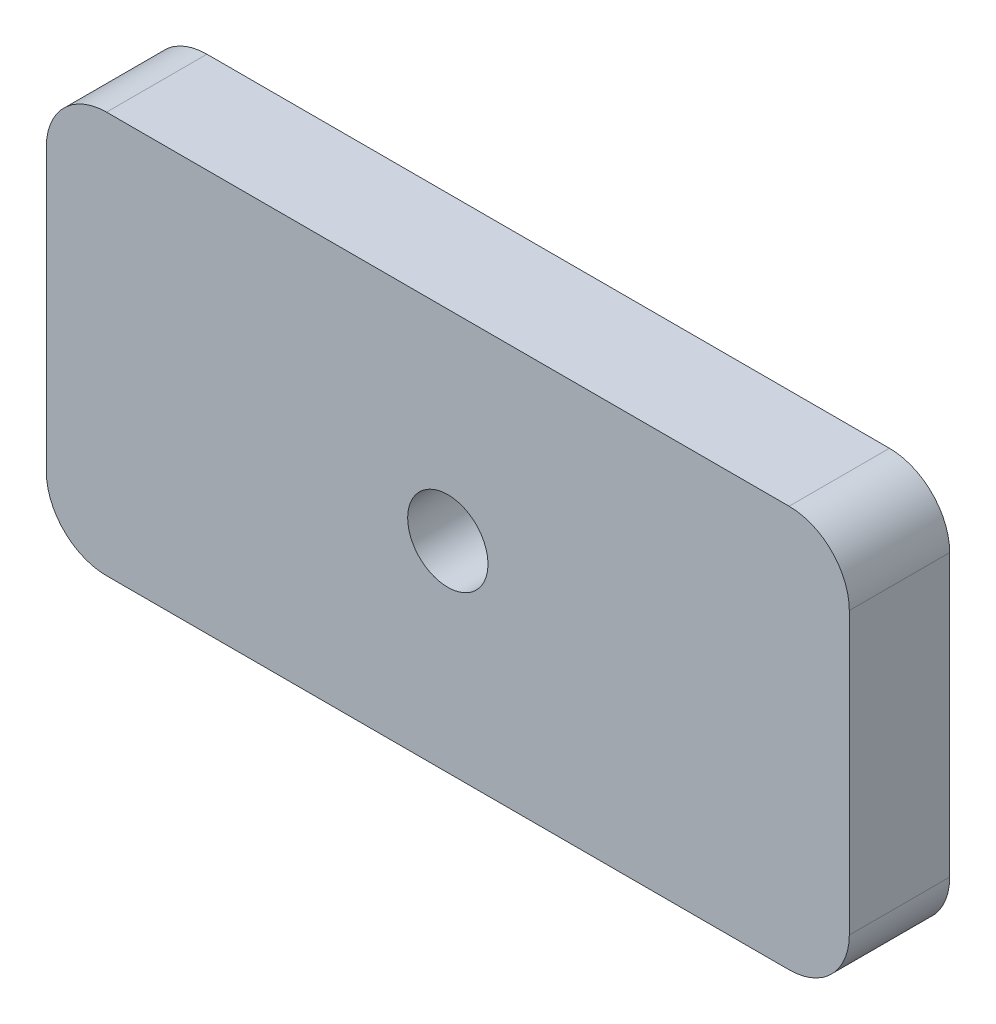
SolidWorks part; units mm, degrees
ref_plane "Front Plane" through (0, 0, 0) normal (0, 0, 1) x (1, 0, 0)
ref_plane "Top Plane" through (0, 0, 0) normal (0, 1, 0) x (1, 0, 0)
ref_plane "Right Plane" through (0, 0, 0) normal (1, 0, 0) x (0, 0, -1)
sketch "Sketch1" plane through (0, 0, 0) normal (0, 0, 1) x (1, 0, 0)
  line L1 (17, 10) -> (-17, 10)
  line L2 (20, 7) -> (20, -7)
  line L3 (17, -10) -> (-17, -10)
  line L4 (-20, 7) -> (-20, -7)
  line L5 (0, -10) -> (0, 10) construction
  line L6 (20, 0) -> (-20, 0) construction
  arc A0 (-17, -10) -> (-20, -7) centre (-17, -7) cw
  arc A1 (20, -7) -> (17, -10) centre (17, -7) cw
  arc A2 (17, 10) -> (20, 7) centre (17, 7) cw
  arc A3 (-17, 10) -> (-20, 7) centre (-17, 7) ccw
  point P0 (0, 0)
  point P6 (-20, -10)
  point P11 (20, 10)
  point P14 (-20, 10)
  dimension "D3" = 3
  dimension "D1" = 20
  dimension "D2" = 40
extrude "Boss-Extrude1" add sketch "Sketch1" along normal blind 5
sketch "Sketch2" plane through (0, 0, 0) normal (0, 0, -1) x (-1, 0, 0)
  circle A0 centre (0, 0) radius 2
  dimension "D1" = 4
extrude "Cut-Extrude1" cut sketch "Sketch2" against normal up to next
